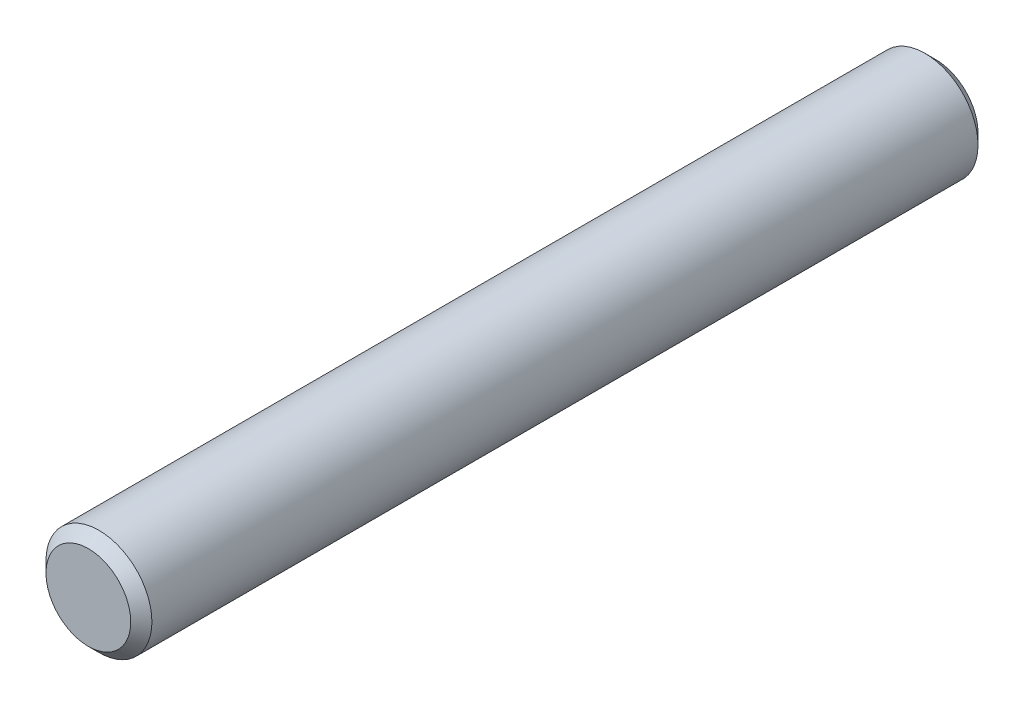
SolidWorks part; units mm, degrees
ref_plane "Front" through (0, 0, 0) normal (0, 0, 1) x (1, 0, 0)
ref_plane "Top" through (0, 0, 0) normal (0, 1, 0) x (1, 0, 0)
ref_plane "Right" through (0, 0, 0) normal (1, 0, 0) x (0, 0, -1)
sketch "Sketch1" plane through (0, 0, 0) normal (0, 0, 1) x (1, 0, 0)
  circle A0 centre (0, 0) radius 1.5875 construction
  dimension "Diameter" = 3.175
sketch "Sketch2" plane through (0, 0, 0) normal (1, 0, 0) x (0, 0, -1)
  line L0 (-12.7, 0) -> (12.7, 0) construction
  line L1 (1.7463, 0) -> (-1.7463, 0) construction
  line L3 (12.7, 1.5875) -> (12.7, -1.5875) construction
  line L4 (-12.7, 1.5875) -> (-12.7, -1.5875) construction
  line L5 (-8.7312, 1.5875) -> (-8.7312, -1.5875) construction
  line L6 (8.7312, 1.5875) -> (8.7312, -1.5875) construction
  point P6 (0, 0)
  point P10 (12.7, 0)
  point P13 (-12.7, 0)
  point P16 (-8.7312, 0)
  point P19 (8.7312, 0)
  dimension "D1" = 3.175
  dimension "Length" = 25.4
  dimension "D2" = 3.9688
  dimension "D3" = 3.9688
sketch "Sketch3" plane through (0, 0, 0) normal (0, 0, 1) x (1, 0, 0)
  line L0 (0, 1.5875) -> (0, -1.5875) construction
  circle A0 centre (0, 0) radius 1.5875
  dimension "D1" = 3.175
extrude "Boss-Extrude1" add sketch "Sketch3" along normal mid plane 25.4
chamfer "Chamfer1" distance 0.3175 angle 45 2 edges at (1.5875, 0, -12.7) (1.5875, 0, 12.7)
equation "\"D1@Sketch2\" = \"Diameter@Sketch1\""
equation "\"D1@Sketch3\" = \"Diameter@Sketch1\""
equation "\"D1@Boss-Extrude1\" = \"Length@Sketch2\""
equation "\"D1@Chamfer1\" = \"Diameter@Sketch1\" * .1"
equation "\"D2@Sketch2\"=\"Diameter@Sketch1\"*1.25"
equation "\"D3@Sketch2\"=\"D2@Sketch2\""
